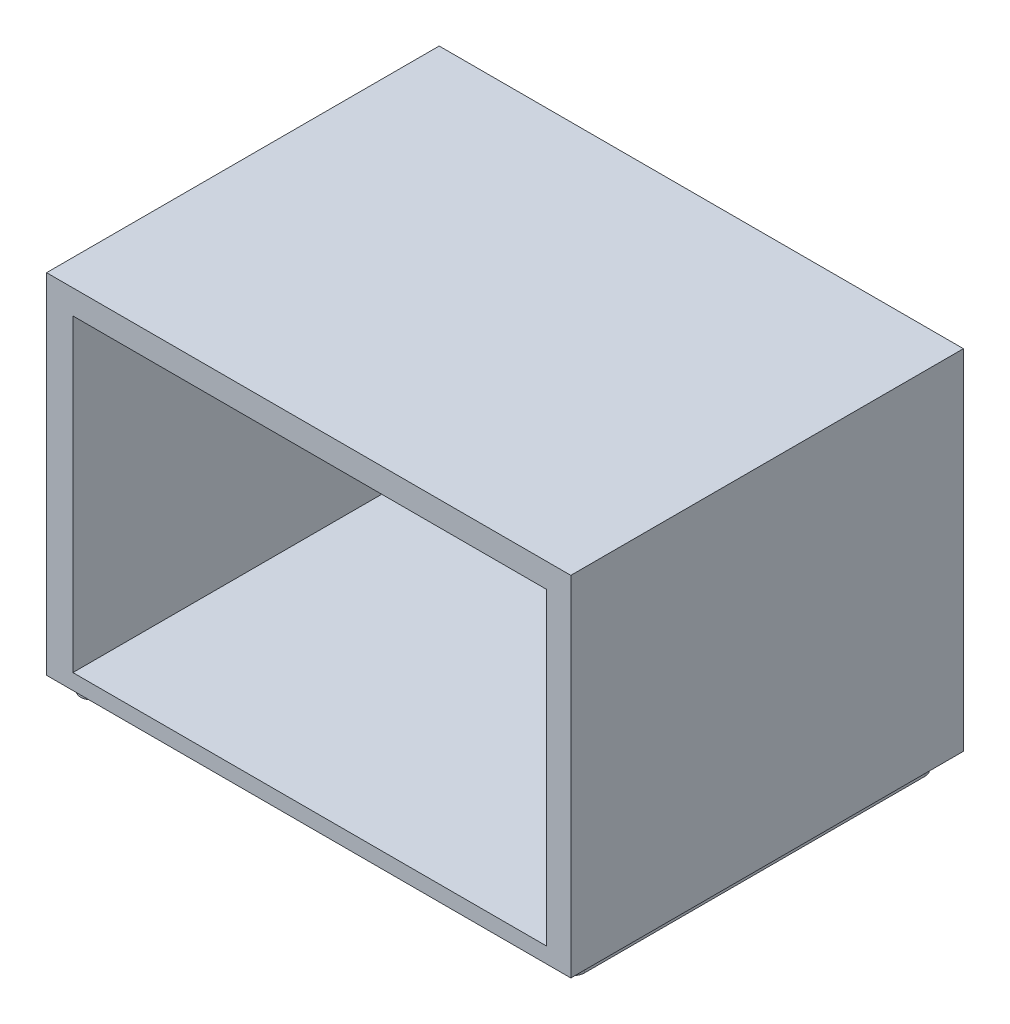
SolidWorks part; units mm, degrees
ref_plane "Ön Düzlem" through (0, 0, 0) normal (0, 0, 1) x (1, 0, 0)
ref_plane "Üst Düzlem" through (0, 0, 0) normal (0, 1, 0) x (1, 0, 0)
ref_plane "Sağ Düzlem" through (0, 0, 0) normal (1, 0, 0) x (0, 0, -1)
sketch "Çizim1" plane through (0, 0, 0) normal (0, 0, 1) x (1, 0, 0)
  line L1 (-115.1277, 32.1473) -> (-15.0582, 32.1473)
  line L2 (-115.1277, 32.1473) -> (-115.1277, -33.8986)
  line L3 (-115.1277, -33.8986) -> (-15.0582, -33.8986)
  line L4 (-15.0582, 32.1473) -> (-15.0582, -33.8986)
  line L5 (-121.1319, 36.9006) -> (-9.054, 36.9006)
  line L6 (-121.1319, 36.9006) -> (-121.1319, -37.6512)
  line L7 (-121.1319, -37.6512) -> (-9.054, -37.6512)
  line L8 (-9.054, 36.9006) -> (-9.054, -37.6512)
extrude "Yükseklik-Ekstrüzyon1" add sketch "Çizim1" along normal blind 83.9349 contours L6 L5 L8 L7
sketch "Çizim2" plane through (0, 0, 83.9349) normal (0, 0, 1) x (1, 0, 0)
  line L1 (-115.5079, 31.7064) -> (-14.2765, 31.7064)
  line L2 (-115.5079, 31.7064) -> (-115.5079, -34.3284)
  line L3 (-115.5079, -34.3284) -> (-14.2765, -34.3284)
  line L4 (-14.2765, 31.7064) -> (-14.2765, -34.3284)
extrude "Kes-Ekstrüzyon2" cut sketch "Çizim2" against normal blind 76.6444
sketch "Çizim3" plane through (0, 0, 7.2905) normal (0, 0, 1) x (1, 0, 0)
  line L1 (-76.2563, 21.729) -> (-36.8113, 21.729)
  line L2 (-76.2563, 21.729) -> (-76.2563, -7.7081)
  line L3 (-76.2563, -7.7081) -> (-36.8113, -7.7081)
  line L4 (-36.8113, 21.729) -> (-36.8113, -7.7081)
extrude "Kes-Ekstrüzyon3" cut sketch "Çizim3" against normal blind 88.138
sketch "Çizim4" plane through (0, -37.6512, 0) normal (0, -1, 0) x (-1, 0, 0)
  line L0 (115.9607, -79.4646) -> (115.9607, -6.6892) construction
  line L1 (113.611, -79.4646) -> (113.611, -6.6892)
  line L2 (118.3103, -79.4646) -> (118.3103, -6.6892)
  line L3 (13.4141, -78.9852) -> (13.4141, -6.2098) construction
  line L4 (11.0645, -78.9852) -> (11.0645, -6.2098)
  line L5 (15.7638, -78.9852) -> (15.7638, -6.2098)
  arc A0 (113.611, -79.4646) -> (118.3103, -79.4646) centre (115.9607, -79.4646) ccw
  arc A1 (118.3103, -6.6892) -> (113.611, -6.6892) centre (115.9607, -6.6892) ccw
  arc A2 (11.0645, -78.9852) -> (15.7638, -78.9852) centre (13.4141, -78.9852) ccw
  arc A3 (15.7638, -6.2098) -> (11.0645, -6.2098) centre (13.4141, -6.2098) ccw
  point P2 (115.9607, -43.0769)
  point P9 (13.4141, -42.5975)
extrude "Yükseklik-Ekstrüzyon2" add sketch "Çizim4" along normal blind 2.54
